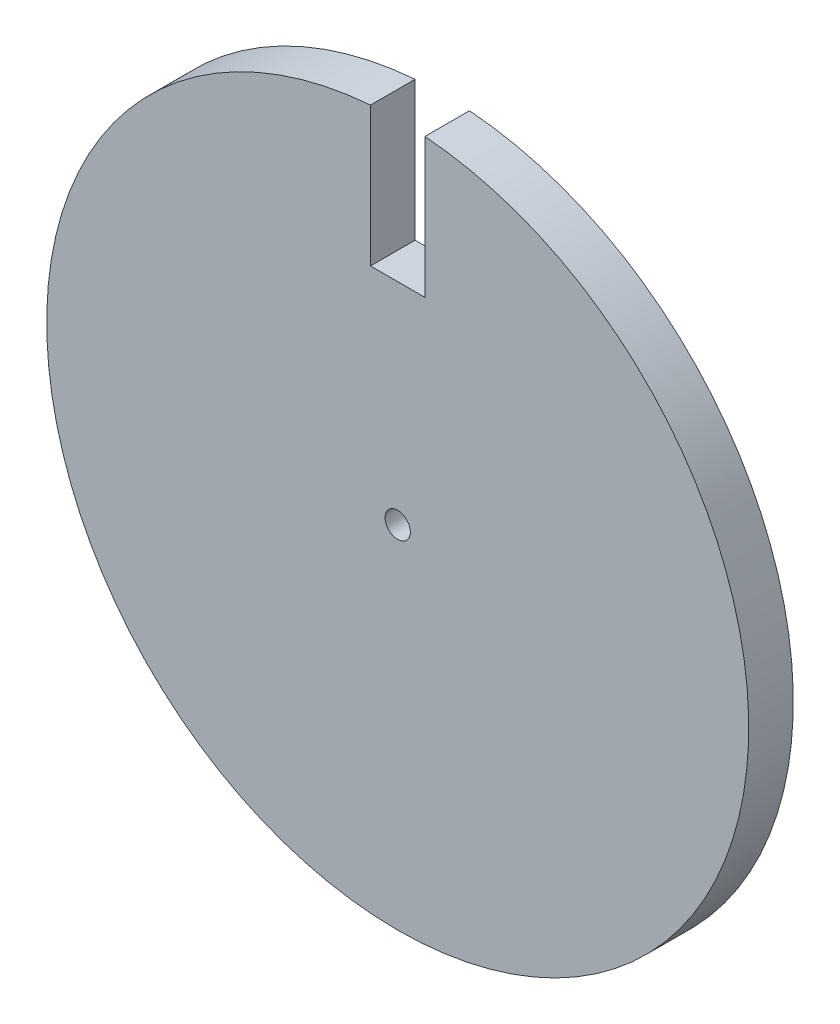
SolidWorks part; units mm, degrees
ref_plane "Front Plane" through (0, 0, 0) normal (0, 0, 1) x (1, 0, 0)
ref_plane "Top Plane" through (0, 0, 0) normal (0, 1, 0) x (1, 0, 0)
ref_plane "Right Plane" through (0, 0, 0) normal (1, 0, 0) x (0, 0, -1)
sketch "Sketch1" plane through (0, 0, 0) normal (0, 0, 1) x (1, 0, 0)
  circle A0 centre (0, 0) radius 25
  circle A1 centre (0, 0) radius 0.9
  dimension "D1" = 1.8
  dimension "D2" = 50
extrude "Boss-Extrude1" add sketch "Sketch1" along normal mid plane 3.175
sketch "Sketch2" plane through (0, 0, -1.5875) normal (0, 0, -1) x (-1, 0, 0)
  line L0 (0, 0) -> (0, 25) construction
  line L1 (1.937, 34.0448) -> (-1.937, 34.0448)
  line L2 (-1.937, 34.0448) -> (-1.937, 15)
  line L3 (-1.937, 15) -> (1.937, 15)
  line L4 (1.937, 15) -> (1.937, 34.0448)
  circle A0 centre (0, 0) radius 25 construction
  point P9 (0, 34.0448)
  dimension "D1" = 15
extrude "Cut-Extrude1" cut sketch "Sketch2" against normal up to body separate body
